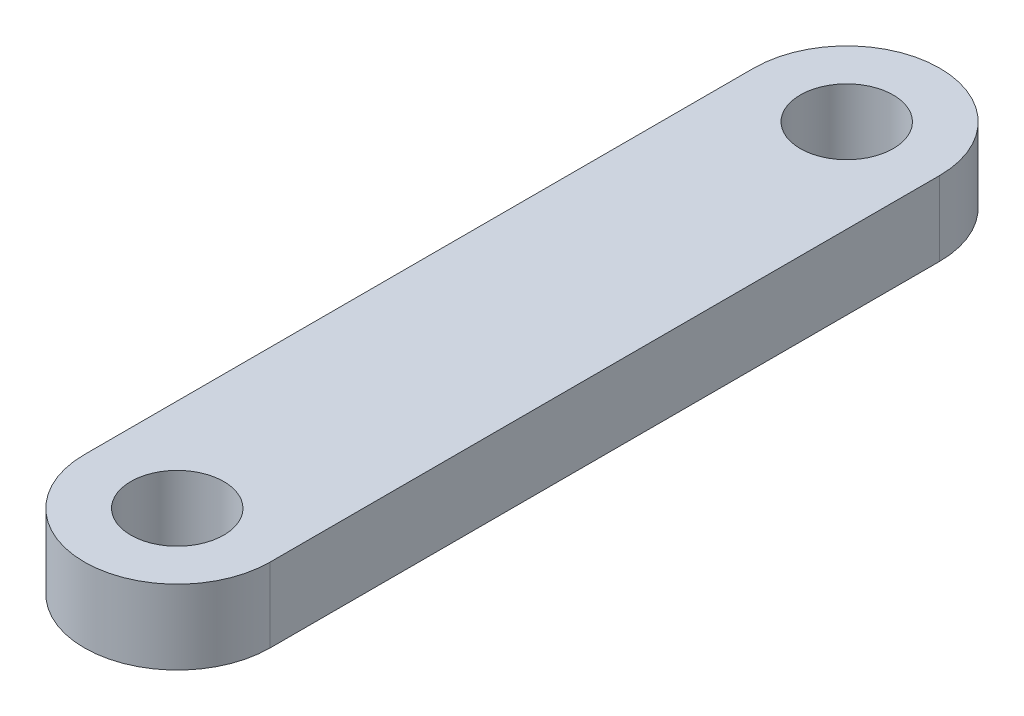
SolidWorks part; units mm, degrees
ref_plane "Front Plane" through (0, 0, 0) normal (0, 0, 1) x (1, 0, 0)
ref_plane "Top Plane" through (0, 0, 0) normal (0, 1, 0) x (1, 0, 0)
ref_plane "Right Plane" through (0, 0, 0) normal (1, 0, 0) x (0, 0, -1)
sketch "Sketch1" plane through (0, 0, 0) normal (0, 1, 0) x (1, 0, 0)
  line L0 (-2.5, 0) -> (-2.5, 18)
  line L1 (2.5, 18) -> (2.5, 0)
  circle A0 centre (0, 18) radius 1
  circle A1 centre (0, 0) radius 1
  arc A2 (-2.5, 0) -> (2.5, 0) centre (0, 0) ccw
  arc A3 (2.5, 18) -> (-2.5, 18) centre (0, 18) ccw
  dimension "D2" = 2
  dimension "D3" = 5
  dimension "D4" = 2
  dimension "D5" = 18
extrude "Boss-Extrude1" add sketch "Sketch1" along normal blind 2
other "Move Face1" face at (0, 2, 1) face at (0, 2, -17) parameters "D1"=0.25
